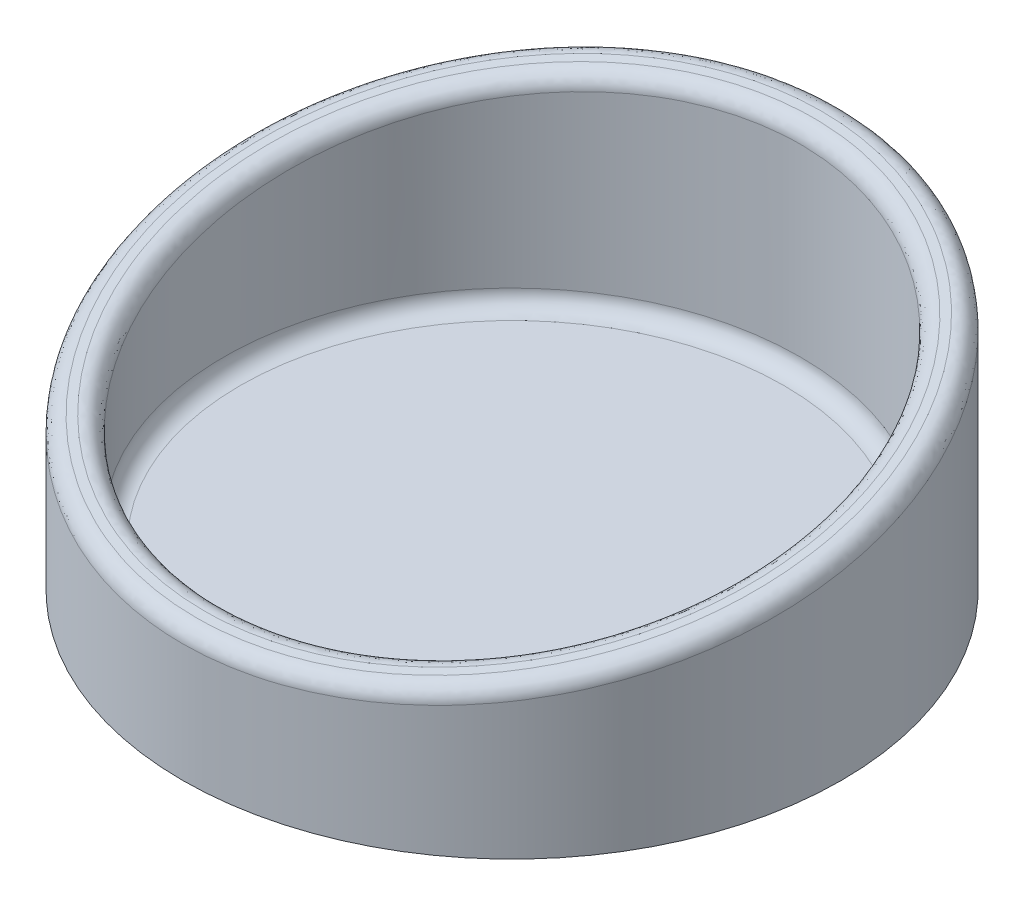
SolidWorks part; units mm, degrees
ref_plane "Front Plane" through (0, 0, 0) normal (0, 0, 1) x (1, 0, 0)
ref_plane "Top Plane" through (0, 0, 0) normal (0, 1, 0) x (1, 0, 0)
ref_plane "Right Plane" through (0, 0, 0) normal (1, 0, 0) x (0, 0, -1)
sketch "Sketch1" plane through (0, 0, 0) normal (0, 1, 0) x (1, 0, 0)
  circle A0 centre (0, 0) radius 25.4
  dimension "D1" = 50.8
extrude "Boss-Extrude1" add sketch "Sketch1" along normal blind 20.32
shell "Shell1" thickness 3.175
sketch "Sketch2" plane through (0, 0, 0) normal (1, 0, 0) x (0, 0, -1)
  line L0 (-25.4, 10.16) -> (-25.4, 20.32)
  line L1 (-25.4, 20.32) -> (-25.4, 0) construction
  line L2 (-25.4, 20.32) -> (25.4, 20.32)
  line L3 (25.4, 20.32) -> (-25.4, 10.16)
  dimension "D1" = 10.16
extrude "Cut-Extrude1" cut sketch "Sketch2" against normal through all both and the other way through all
fillet "Fillet1" radius 1.27 3 edges at (0, 10.16, 25.4) (0, 10.795, 22.225) (0, 3.175, 22.225)
